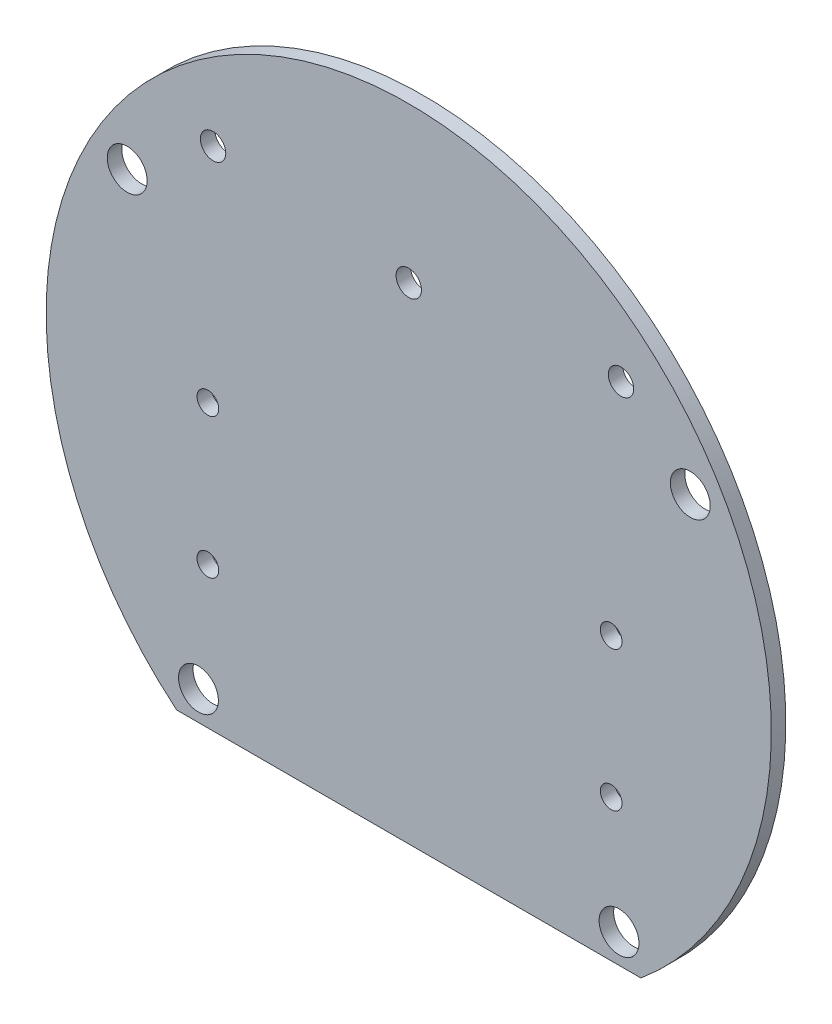
SolidWorks part; units mm, degrees
ref_plane "Plano frontal" through (0, 0, 0) normal (0, 0, 1) x (1, 0, 0)
ref_plane "Plano superior" through (0, 0, 0) normal (0, 1, 0) x (1, 0, 0)
ref_plane "Plano direito" through (0, 0, 0) normal (1, 0, 0) x (0, 0, -1)
sketch "Esboço1" plane through (0, 0, 0) normal (0, 0, 1) x (1, 0, 0)
  circle A0 centre (0, 0) radius 50
  dimension "D1" = 100
extrude "Ressalto-extrusão1" add sketch "Esboço1" along normal blind 2
sketch "Esboço2" plane through (0, 0, 2) normal (0, 0, 1) x (1, 0, 0)
  line L0 (0, 0) -> (0, 68.6386) construction
  line L1 (-61.9657, 0) -> (66.0984, 0) construction
  line L2 (-61.9657, -34.4093) -> (66.0984, -34.4093) construction
  circle A4 centre (-29, -34.4093) radius 2.75
  circle A5 centre (29, -34.4093) radius 2.75
  circle A6 centre (-38.8242, 22.7526) radius 2.75
  circle A7 centre (38.8242, 22.7526) radius 2.75
  point P9 (2.9328, -3.8481)
  dimension "D1" = 58
  dimension "D4" = 45
  dimension "D2" = 45
  dimension "D8" = 5.5
  dimension "D9" = 5.5
  dimension "D10" = 5.5
  dimension "D11" = 5.5
  dimension "D3" = 45
  dimension "D5" = 45
  dimension "D6" = 58
  dimension "D7" = 58
extrude "Corte-extrusão1" cut sketch "Esboço2" against normal blind 2
sketch "Esboço4" plane through (0, 0, 2) normal (0, 0, 1) x (1, 0, 0)
  line L0 (-40.7239, -38.4093) -> (44.5707, -38.4093)
  line L1 (-40.7239, -38.4093) -> (1.9234, -68.0022)
  line L2 (1.9234, -68.0022) -> (44.5707, -38.4093)
  circle A0 centre (-29, -34.4093) radius 2.75 construction
  dimension "D1" = 4
extrude "Corte-extrusão2" cut sketch "Esboço4" against normal blind 10 and the other way through all
sketch "Esboço5" plane through (0, 0, 0) normal (0, 0, -1) x (-1, 0, 0)
  line L0 (65.401, 0) -> (-65.401, 0) construction
  line L2 (0, 53.6175) -> (0, -45.5551) construction
  circle A1 centre (-27.91, -18.86) radius 1.5
  circle A2 centre (27.7, -18.86) radius 1.5
  circle A3 centre (27.7, 0.44) radius 1.5
  circle A4 centre (-27.91, 0.44) radius 1.5
  circle A5 centre (26.98, 31.44) radius 1.75
  circle A6 centre (0, 28.6) radius 1.75
  circle A7 centre (-29.27, 31.44) radius 1.75
  point P4 (0, 0)
  dimension "D1" = 26.98
  dimension "D11" = 28.6
  dimension "D12" = 29.27
  dimension "D2" = 31.44
  dimension "D3" = 0.44
  dimension "D4" = 0.44
  dimension "D5" = 18.86
  dimension "D6" = 27.91
  dimension "D7" = 27.91
  dimension "D8" = 27.7
  dimension "D9" = 27.7
  dimension "D10" = 18.86
extrude "Corte-extrusão3" cut sketch "Esboço5" against normal blind 10
